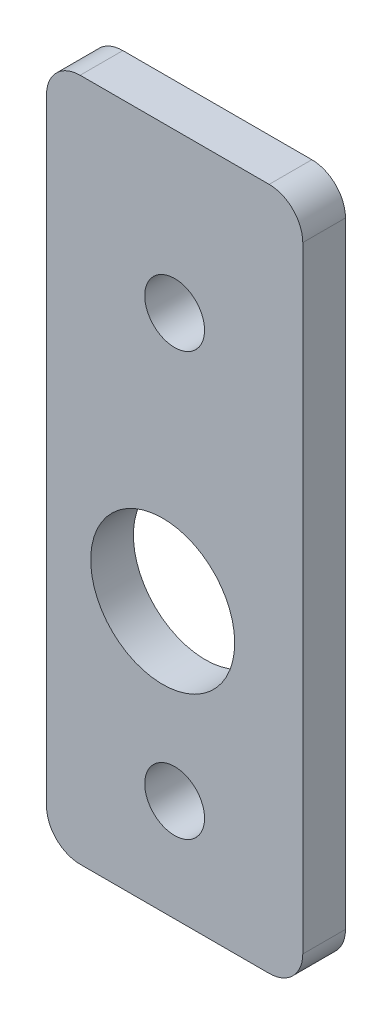
SolidWorks part; units mm, degrees
material "Acrylic (Medium-high impact)"
ref_plane "Front Plane" through (0, 0, 0) normal (0, 0, 1) x (1, 0, 0)
ref_plane "Top Plane" through (0, 0, 0) normal (0, 1, 0) x (1, 0, 0)
ref_plane "Right Plane" through (0, 0, 0) normal (1, 0, 0) x (0, 0, -1)
sketch "Sketch1" plane through (0, 0, 0) normal (0, 0, 1) x (1, 0, 0)
  line L4 (38.1, -101.6) -> (0, -101.6)
  line L5 (38.1, 0) -> (0, 0)
  line L6 (38.1, -101.6) -> (38.1, 0)
  line L7 (0, -101.6) -> (0, 0)
  circle A0 centre (17.272, -61.6) radius 10.7061
  dimension "D2" = 21.4122
  dimension "D1" = 101.6
  dimension "D3" = 40
  dimension "D4" = 17.272
  dimension "D5" = 38.1
extrude "Boss-Extrude1" add sketch "Sketch1" along normal blind 6.35
sketch "Sketch2" plane through (0, 0, 6.35) normal (0, 0, 1) x (1, 0, 0)
  line L0 (19.05, 0) -> (19.05, -101.6) construction
  line L1 (38.1, 0) -> (0, 0) construction
  line L2 (0, -101.6) -> (38.1, -101.6) construction
  circle A0 centre (19.05, -23.5884) radius 4.445
  circle A1 centre (19.05, -86.4255) radius 4.445
  dimension "D1" = 8.89
  dimension "D2" = 15.1745
  dimension "D3" = 23.5884
extrude "Cut-Extrude1" cut sketch "Sketch2" against normal up to next
fillet "Fillet1" radius 5 4 edges at (38.1, 0, 3.175) (38.1, -101.6, 3.175) (0, -101.6, 3.175) (0, 0, 3.175)
